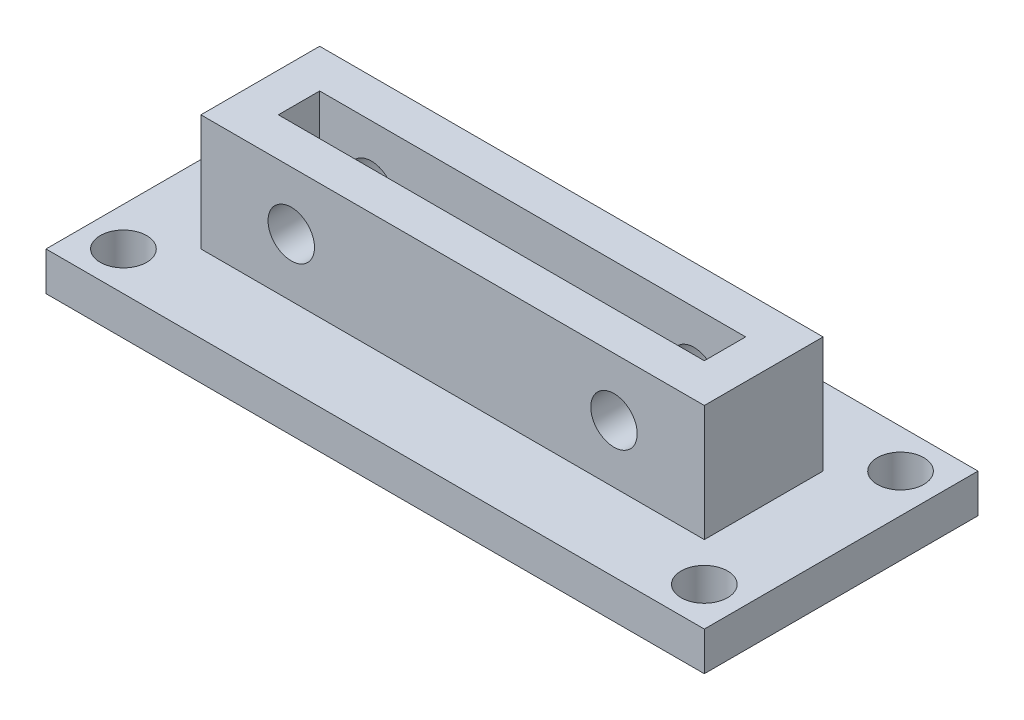
SolidWorks part; units mm, degrees
ref_plane "Front Plane" through (0, 0, 0) normal (0, 0, 1) x (1, 0, 0)
ref_plane "Top Plane" through (0, 0, 0) normal (0, 1, 0) x (1, 0, 0)
ref_plane "Right Plane" through (0, 0, 0) normal (1, 0, 0) x (0, 0, -1)
sketch "Sketch1" plane through (0, 0, 0) normal (0, 1, 0) x (1, 0, 0)
  line L1 (0, 0) -> (51, 0)
  line L2 (0, 0) -> (0, 21.2)
  line L3 (0, 21.2) -> (51, 21.2)
  line L4 (51, 0) -> (51, 21.2)
  dimension "D1" = 51
  dimension "D2" = 21.2
extrude "Boss-Extrude1" add sketch "Sketch1" along normal blind 3
sketch "Sketch2" plane through (0, 3, 0) normal (0, 1, 0) x (1, 0, 0)
  line L0 (0, 21.2) -> (0, 0) construction
  line L1 (6, 15.2) -> (45, 15.2)
  line L2 (6, 15.2) -> (6, 6)
  line L3 (6, 6) -> (45, 6)
  line L4 (45, 15.2) -> (45, 6)
  line L5 (9, 12.2) -> (42, 12.2)
  line L6 (9, 12.2) -> (9, 9)
  line L7 (9, 9) -> (42, 9)
  line L8 (42, 12.2) -> (42, 9)
  line L9 (0, 21.2) -> (0, 0) construction
  line L10 (0, 0) -> (51, 0) construction
  line L11 (0, 0) -> (51, 0) construction
  point P10 (25.5, 12.2)
  point P11 (25.5, 15.2)
  point P13 (0, 10.6)
  point P14 (6, 10.6)
  point P16 (25.5, 0)
  point P17 (25.5, 6)
  dimension "D1" = 3.2
  dimension "D2" = 3
  dimension "D3" = 3
  dimension "D4" = 33
  dimension "D5" = 39
extrude "Boss-Extrude2" add sketch "Sketch2" along normal blind 9
hole_wizard "M3 Clearance Hole1" positions "Sketch4" profile "Sketch5" hole size "M3" standard "ANSI Metric" end condition through all
sketch "Sketch4" plane through (0, 3, 0) normal (0, 1, 0) x (1, 0, 0)
  line L0 (25.5, 21.2) -> (25.5, 0) construction
  line L1 (51, 21.2) -> (0, 21.2) construction
  line L2 (0, 0) -> (51, 0) construction
  line L4 (0, 10.6) -> (51, 10.6) construction
  line L5 (0, 21.2) -> (0, 0) construction
  line L6 (51, 0) -> (51, 21.2) construction
  line L7 (6, 15.2) -> (6, 21.2) construction
  line L9 (6, 15.2) -> (0, 15.2) construction
  point P0 (3, 18.2)
  point P31 (48, 18.2)
  point P47 (6, 18.2)
  point P48 (3, 15.2)
  point P51 (48, 3)
  point P52 (3, 3)
  dimension "D1" = 3
  dimension "D2" = 3
  dimension "D3" = 45
sketch "Sketch5" plane through (3, 3, -18.2) normal (1, 0, 0) x (0, 0, 1)
  line L0 (0, 0) -> (0, 3)
  line L1 (0, 3) -> (1.8, 3)
  line L2 (1.8, 3) -> (1.8, 0)
  line L5 (1.8, 0) -> (0, 0)
  line L11 (0, -6.35) -> (0, 107.95) construction
  dimension "Thru Hole Dia." = 3.6
  dimension "Thru Hole Depth" = 3
hole_wizard "M3 Clearance Hole2" positions "Sketch6" profile "Sketch7" hole size "M3" standard "ANSI Metric" end condition through all
sketch "Sketch6" plane through (0, 0, -6) normal (0, 0, 1) x (1, 0, 0)
  line L2 (9, 12) -> (42, 12) construction
  line L3 (9, 12) -> (42, 12) construction
  line L4 (13, 7.5) -> (38, 7.5) construction
  line L6 (9, 12) -> (9, 3) construction
  line L7 (9, 12) -> (9, 3) construction
  point P3 (13, 7.5)
  point P5 (38, 7.5)
  point P18 (25.5, 7.5)
  point P19 (25.5, 12)
  point P24 (9, 7.5)
  dimension "D1" = 4
sketch "Sketch7" plane through (13, 7.5, -6) normal (1, 0, 0) x (0, -1, 0)
  line L0 (0, 0) -> (0, 15.2)
  line L1 (0, 15.2) -> (1.8, 15.2)
  line L2 (1.8, 15.2) -> (1.8, 0)
  line L5 (1.8, 0) -> (0, 0)
  line L11 (0, -6.35) -> (0, 107.95) construction
  dimension "Thru Hole Dia." = 3.6
  dimension "Thru Hole Depth" = 15.2
equation "\"A\"=9.9176"
